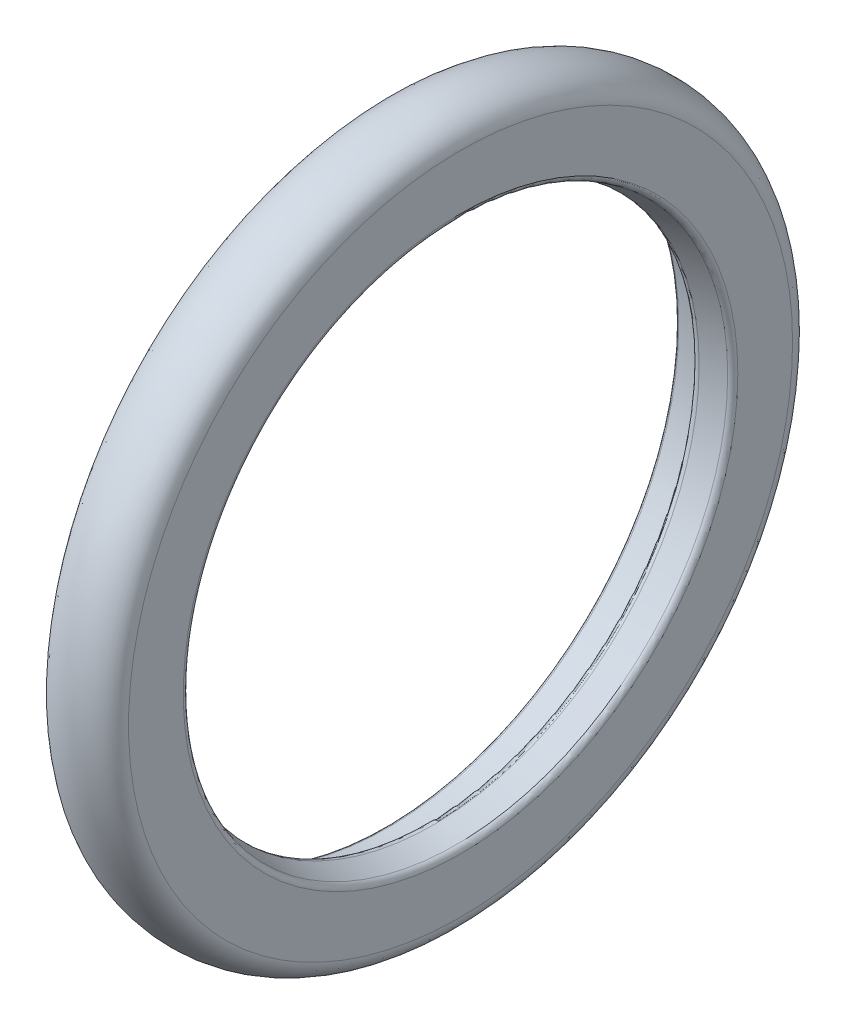
SolidWorks part; units mm, degrees
ref_plane "Front Plane" through (0, 0, 0) normal (0, 0, 1) x (1, 0, 0)
ref_plane "Top Plane" through (0, 0, 0) normal (0, 1, 0) x (1, 0, 0)
ref_plane "Right Plane" through (0, 0, 0) normal (1, 0, 0) x (0, 0, -1)
ref_axis "Axis1" through (88.99, 0, 0) along (-1, 0, 0)
sketch "Sketch1" plane through (0, 0, 0) normal (0, 1, 0) x (1, 0, 0)
  line L0 (0, 0) -> (0, 28) construction
  line L1 (-3.175, 28) -> (-3.175, 24.75)
  line L2 (-2.925, 24.5) -> (-0.5587, 24.5)
  line L3 (-0.0757, 24.1294) -> (0.295, 22.7459)
  line L4 (0.9074, 22.3924) -> (2.8044, 22.9007)
  line L5 (3.175, 23.3837) -> (3.175, 28)
  arc A0 (-0.5587, 24.5) -> (-0.0757, 24.1294) centre (-0.5587, 24) cw
  arc A1 (2.8044, 22.9007) -> (3.175, 23.3837) centre (2.675, 23.3837) ccw
  arc A2 (0.295, 22.7459) -> (0.9074, 22.3924) centre (0.778, 22.8754) ccw
  arc A3 (-3.175, 24.75) -> (-2.925, 24.5) centre (-2.925, 24.75) ccw
  ellipse E0 centre (0, 28) end of major axis (3.175, 28) minor radius 2 (-3.175, 28) -> (3.175, 28) cw
  point P15 (-0.175, 24.5)
  point P18 (3.175, 23)
  point P23 (-3.175, 24.5)
  dimension "D8" = 0.5
  dimension "D9" = 0.25
  dimension "D1" = 28
  dimension "D2" = 2
  dimension "D3" = 6.35
  dimension "D4" = 3.5
  dimension "D5" = 3
  dimension "D6" = 105
  dimension "D7" = 5
revolve "Revolve1" add sketch "Sketch1" angle 360 about axis through (88.99, 0, 0) along (-1, 0, 0)
